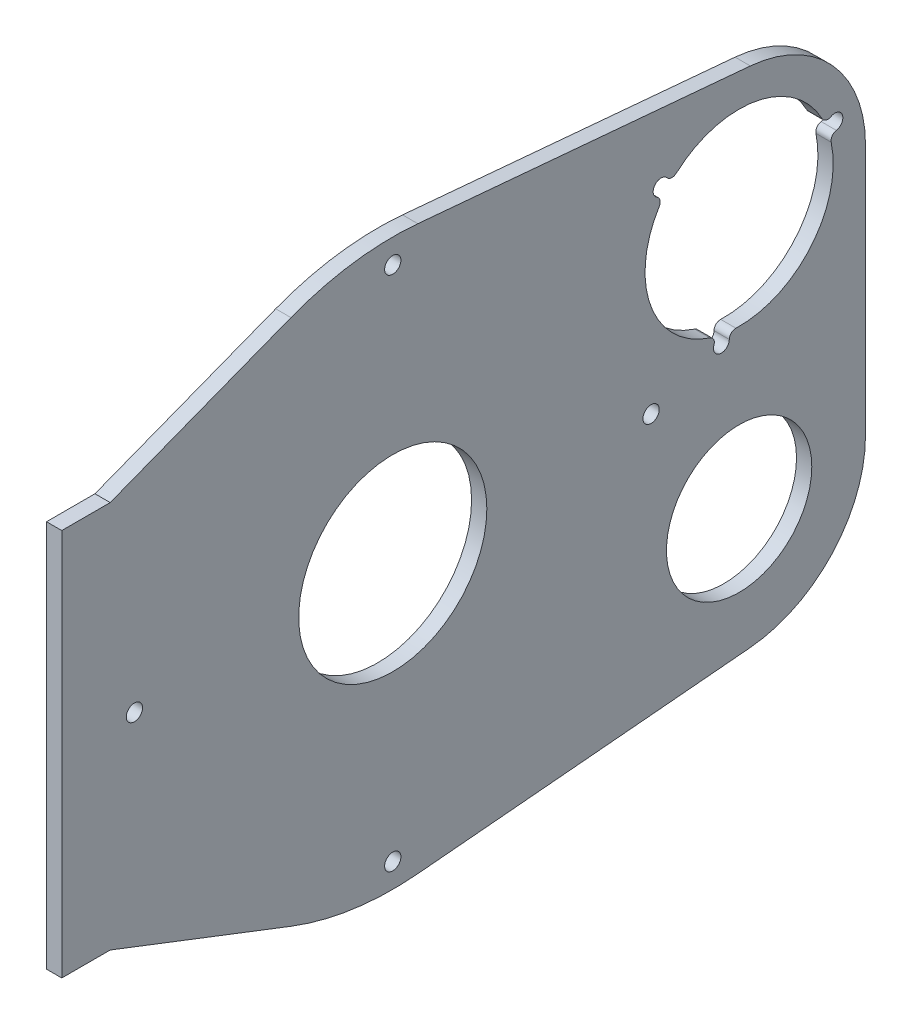
SolidWorks part; units mm, degrees
ref_plane "Front Plane" through (0, 0, 0) normal (0, 0, 1) x (1, 0, 0)
ref_plane "Top Plane" through (0, 0, 0) normal (0, 1, 0) x (1, 0, 0)
ref_plane "Right Plane" through (0, 0, 0) normal (1, 0, 0) x (0, 0, -1)
sketch "Sketch1" plane through (0, 0, 0) normal (1, 0, 0) x (0, 0, -1)
  line L0 (0, 0) -> (68.1072, 24.765) construction
  line L1 (0, 0) -> (68.1072, -24.765) construction
  line L2 (-41.684, 0) -> (86.822, 0) construction
  line L3 (-55.5625, 38.1) -> (-20.0222, 51.8295)
  line L4 (-65.0875, 38.1) -> (-55.5625, 38.1)
  line L5 (-65.0875, 38.1) -> (-65.0875, -38.1)
  line L6 (-65.0875, -38.1) -> (-55.5625, -38.1)
  line L7 (-55.5625, 38.1) -> (-55.5625, -38.1)
  line L8 (4.9318, 55.3432) -> (70.3129, 49.5169)
  line L9 (92.9572, 24.765) -> (92.9572, -24.765)
  line L10 (70.3129, -49.5169) -> (4.9318, -55.3432)
  line L11 (-20.0222, -51.8295) -> (-55.5625, -38.1)
  circle A0 centre (0, 0) radius 14.2875 construction
  circle A1 centre (68.1072, 24.765) radius 18.5
  circle A2 centre (68.1072, -24.765) radius 14.2875
  circle A3 centre (0, 0) radius 55.5625 construction
  circle A4 centre (0, 0) radius 18.5
  circle A5 centre (68.1072, 24.765) radius 30.48 construction
  circle A6 centre (68.1072, -24.765) radius 19.05 construction
  arc A7 (70.3129, 49.5169) -> (92.9572, 24.765) centre (68.1072, 24.765) cw
  arc A8 (92.9572, -24.765) -> (70.3129, -49.5169) centre (68.1072, -24.765) cw
  arc A9 (-20.0222, 51.8295) -> (4.9318, 55.3432) centre (0, 0) cw
  arc A10 (4.9318, -55.3432) -> (-20.0222, -51.8295) centre (0, 0) cw
  circle A11 centre (0, 50.8) radius 1.6
  circle A12 centre (0, 0) radius 46.5 construction
  circle A13 centre (50.8, 0) radius 1.6
  circle A14 centre (0, -50.8) radius 1.6
  circle A15 centre (-50.8, 0) radius 1.6
  point P17 (-65.0875, 0)
  point P26 (-43.7081, -5.9124)
  point P30 (0, 0)
  point P38 (0, 0)
  dimension "D1" = 111.125
  dimension "D2" = 28.575
  dimension "D3" = 37
  dimension "D5" = 60.96
  dimension "D6" = 38.1
  dimension "D8" = 6.35
  dimension "D11" = 3.2
  dimension "D13" = 93
  dimension "D4" = 72.47
  dimension "D7" = 9.525
  dimension "D10" = 76.2
  dimension "D12" = 50.8
  dimension "D14" = 4
extrude "Boss-Extrude1" add sketch "Sketch1" along normal blind 3 contours A10 L10 A8 L9 A7 L8 A9 L3 L7 L11 A15 A14 A13 A11 A4 A2 A1 | L7 L4 L5 L6
sketch "Sketch2" plane through (0, 0, 0) normal (-1, 0, 0) x (0, 0, 1)
  line L0 (0, 0) -> (-68.1072, 24.765) construction
  arc A0 (-86.1821, 32.9629) -> (-87.2262, 30.0914) centre (-86.9502, 31.6166) ccw
  circle A1 centre (-86.9502, 31.6166) radius 2.75 construction
  circle A2 centre (-68.1072, 24.765) radius 18.5 construction
  arc A3 (-87.2262, 30.0914) -> (-86.2096, 28.5798) centre (-87.4523, 28.8417) cw
  arc A4 (-86.1821, 32.9629) -> (-84.432, 33.4685) centre (-85.5527, 34.066) ccw
  arc A5 (-84.432, 33.4685) -> (-86.2096, 28.5798) centre (-68.1072, 24.765) ccw
  point P4 (-86.9502, 31.6166)
  point P13 (-85.5003, 30.8442)
  dimension "D1" = 3.1
  dimension "D2" = 5.5
  dimension "D3" = 1.27
extrude "Cut-Extrude1" cut sketch "Sketch2" against normal through all both and the other way through all
pattern_circular "CirPattern1" count 3 over 360 about axis through (0, 24.765, -68.1072) along (1, 0, 0) of "Cut-Extrude1"
